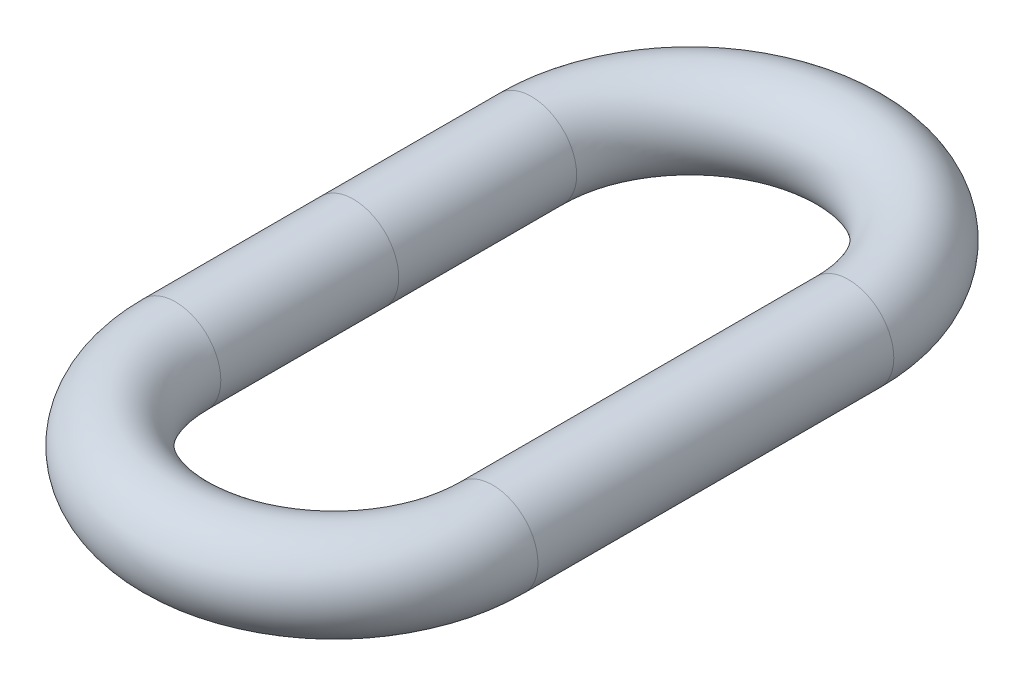
SolidWorks part; units mm, degrees
ref_plane "Front" through (0, 0, 0) normal (0, 0, 1) x (1, 0, 0)
ref_plane "Top" through (0, 0, 0) normal (0, 1, 0) x (1, 0, 0)
ref_plane "Right" through (0, 0, 0) normal (1, 0, 0) x (0, 0, -1)
sketch "Sketch1" plane through (0, 0, 0) normal (0, 1, 0) x (1, 0, 0)
  line L0 (-114.3, -99.7453) -> (-114.3, 99.7453)
  line L1 (114.3, 99.7453) -> (114.3, -99.7453)
  line L2 (0, 99.7453) -> (0, -99.7453) construction
  arc A0 (-114.3, 99.7453) -> (114.3, 99.7453) centre (0, 99.7453) cw
  arc A1 (114.3, -99.7453) -> (-114.3, -99.7453) centre (0, -99.7453) cw
  circle A2 centre (0, 0) radius 177.8 construction
  dimension "D3" = 355.6
  dimension "D1" = 228.6
sketch "Sketch2" plane through (0, 0, 0) normal (0, 0, 1) x (1, 0, 0)
  line L0 (-88.9, 0) -> (-114.3, 0) construction
  line L1 (-114.3, 0) -> (-114.3, 25.4) construction
  circle A0 centre (-88.9, 25.4) radius 25.4
  point P2 (0, 0)
  dimension "D1" = 50.8
sweep "Sweep1" add profiles "Sketch2" path "Sketch1"
equation "\"D2@Sketch1\"=\"D3@Sketch1\"*3.14159"
